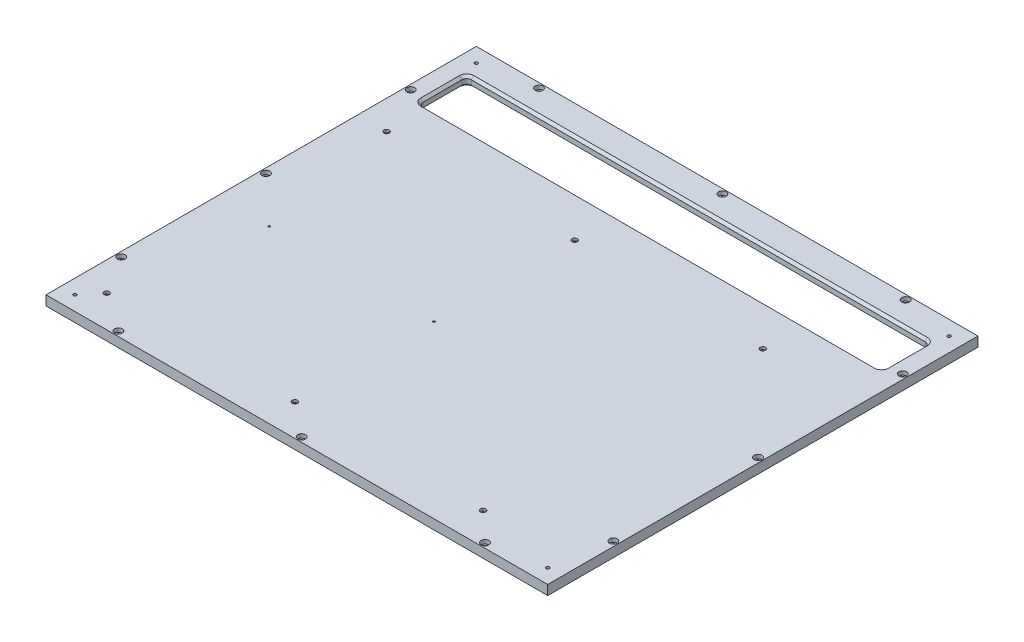
SolidWorks part; units mm, degrees
material "Bakelite Black"
ref_plane "Front" through (0, 0, 0) normal (0, 0, 1) x (1, 0, 0)
ref_plane "Top" through (0, 0, 0) normal (0, 1, 0) x (1, 0, 0)
ref_plane "Right" through (0, 0, 0) normal (1, 0, 0) x (0, 0, -1)
sketch "Sketch1" plane through (0, 0, 0) normal (0, 1, 0) x (1, 0, 0)
  line L1 (0, 0) -> (520, 0)
  line L2 (0, 0) -> (0, 446)
  line L3 (0, 446) -> (520, 446)
  line L4 (520, 0) -> (520, 446)
  dimension "D1" = 520
  dimension "D2" = 446
extrude "Boss-Extrude1" add sketch "Sketch1" along normal blind 10
sketch "Sketch4" plane through (0, 10, 0) normal (0, 1, 0) x (1, 0, 0)
  line L0 (520, 446) -> (0, 446) construction
  line L1 (500, 366) -> (20, 366)
  line L2 (500, 366) -> (500, 416)
  line L3 (500, 416) -> (20, 416)
  line L4 (20, 366) -> (20, 416)
  line L6 (260, 416) -> (260, 0) construction
  line L7 (20, 391) -> (500, 391) construction
  line L8 (0, 0) -> (520, 0) construction
  dimension "D1" = 240
  dimension "D2" = 30
  dimension "D3" = 50
extrude "Cut-Extrude1" cut sketch "Sketch4" against normal blind 10
fillet "Fillet1" radius 5 4 edges at (500, 5, -366) (20, 5, -416) (500, 5, -416) (20, 5, -366)
chamfer "Chamfer1" distance 2.5 angle 45 16 edges at (21.4645, 10, -367.4645) (260, 10, -366) (498.5355, 10, -367.4645) (500, 10, -391) (498.5355, 10, -414.5355) (260, 10, -416) (21.4645, 10, -414.5355) (20, 10, -391) (21.4645, 0, -367.4645) (20, 0, -391) (21.4645, 0, -414.5355) (260, 0, -416) (498.5355, 0, -414.5355) (500, 0, -391) (498.5355, 0, -367.4645) (260, 0, -366)
ref_plane "Plane1" through (260, 0, 0) normal (-1, 0, 0) x (0, 0, 1)
ref_plane "Plane2" through (0, 0, -223) normal (0, 0, 1) x (1, 0, 0)
hole_wizard "CBORE for M4 SHCS1" positions "Sketch5" profile "Sketch6" counterbore size "M4" standard "ANSI Metric"
sketch "Sketch5" plane through (0, 10, 0) normal (0, 1, 0) x (1, 0, 0)
  line L0 (260, 5.5) -> (260, -5.5) construction
  line L1 (-5.5, 223) -> (5.5, 223) construction
  line L3 (0, 0) -> (520, 0) construction
  line L4 (520, 446) -> (0, 446) construction
  line L5 (0, 446) -> (0, 0) construction
  line L6 (520, 0) -> (520, 446) construction
  point P0 (5, 373)
  point P2 (5, 223)
  point P4 (5, 73)
  point P6 (70, 5)
  point P8 (260, 5)
  point P10 (450, 5)
  point P12 (515, 73)
  point P14 (515, 223)
  point P16 (515, 373)
  point P18 (450, 441)
  point P20 (260, 441)
  point P22 (70, 441)
  dimension "D1" = 150
  dimension "D2" = 150
  dimension "D3" = 190
  dimension "D4" = 190
  dimension "D5" = 5
  dimension "D6" = 5
  dimension "D7" = 5
  dimension "D8" = 5
sketch "Sketch6" plane through (5, 10, -373) normal (1, 0, 0) x (0, 0, 1)
  line L0 (0, 0) -> (0, 13.3519)
  line L1 (0, 13.3519) -> (2.25, 12)
  line L2 (2.25, 12) -> (2.25, 4)
  line L3 (2.25, 4) -> (4, 4)
  line L4 (4, 4) -> (4, 0)
  line L5 (4, 0) -> (0, 0)
  line L10 (0, 13.3519) -> (-2.25, 12) construction
  line L11 (0, -6.35) -> (0, 107.95) construction
  dimension "Hole Dia." = 4.5
  dimension "Hole Depth" = 12
  dimension "C'Bore Dia." = 8
  dimension "C'Bore Depth" = 4
  dimension "Drill Angle" = 118
hole_wizard "M4x0.7 Tapped Hole1" positions "Sketch7" profile "Sketch8" tap size "M4x0.7" standard "ANSI Metric" end condition through all
sketch "Sketch7" plane through (0, 10, 0) normal (0, 1, 0) x (1, 0, 0)
  line L0 (520, 446) -> (0, 446) construction
  line L1 (0, 446) -> (0, 0) construction
  line L2 (520, 0) -> (520, 446) construction
  line L3 (0, 0) -> (520, 0) construction
  point P0 (15, 431)
  point P2 (505, 431)
  point P4 (15, 15)
  point P6 (505, 15)
  dimension "D1" = 15
  dimension "D2" = 15
  dimension "D3" = 15
  dimension "D4" = 15
sketch "Sketch8" plane through (15, 10, -431) normal (1, 0, 0) x (0, 0, 1)
  line L0 (0, 0) -> (0, 10)
  line L1 (0, 10) -> (1.65, 10)
  line L2 (1.65, 10) -> (1.65, 0)
  line L5 (1.65, 0) -> (0, 0)
  line L11 (0, -6.35) -> (0, 107.95) construction
  dimension "Thru Tap Drill Dia." = 3.3
  dimension "Thru Tap Drill Depth" = 10
cosmetic thread "Hole Thread1" parameters "D2"=4
cosmetic thread "Hole Thread2" parameters "D2"=4
cosmetic thread "Hole Thread3" parameters "D2"=4
cosmetic thread "Hole Thread4" parameters "D2"=4
hole_wizard "CBORE for M2.5 SHCS1" positions "Sketch9" profile "Sketch10" counterbore size "M2.5" standard "ANSI Metric" end condition through all
sketch "Sketch9" plane through (0, 10, 0) normal (0, 1, 0) x (1, 0, 0)
  line L0 (-5.5, 223) -> (5.5, 223) construction
  line L1 (260, 5.5) -> (260, -5.5) construction
  point P0 (30, 33)
  point P7 (225, 33)
  point P9 (420, 33)
  point P11 (420, 323)
  point P13 (225, 323)
  point P15 (30, 323)
  dimension "D1" = 190
  dimension "D2" = 230
  dimension "D3" = 290
  dimension "D4" = 195
  dimension "D5" = 195
sketch "Sketch10" plane through (30, 10, -33) normal (1, 0, 0) x (0, 0, 1)
  line L0 (0, 0) -> (0, 10)
  line L1 (0, 10) -> (1.45, 10)
  line L3 (1.45, 10) -> (1.45, 2.5)
  line L4 (1.45, 2.5) -> (2.75, 2.5)
  line L5 (2.75, 2.5) -> (2.75, 0)
  line L7 (2.75, 0) -> (0, 0)
  line L11 (0, -6.35) -> (0, 107.95) construction
  dimension "Thru Hole Dia." = 2.9
  dimension "Thru Hole Depth" = 10
  dimension "C'Bore Dia." = 5.5
  dimension "C'Bore Depth" = 2.5
hole_wizard "M2.5x0.45 Tapped Hole1" positions "Sketch11" profile "Sketch12" tap size "M2.5x0.45" standard "ANSI Metric" end condition through all
sketch "Sketch11" plane through (0, 10, 0) normal (0, 1, 0) x (1, 0, 0)
  line L0 (-5.5, 223) -> (5.5, 223) construction
  line L1 (260, 5.5) -> (260, -5.5) construction
  point P0 (54.288, 177.0876)
  point P2 (225.088, 177.0876)
  dimension "D1" = 170.8
  dimension "D2" = 45.9124
  dimension "D3" = 205.712
sketch "Sketch12" plane through (54.288, 10, -177.0876) normal (1, 0, 0) x (0, 0, 1)
  line L0 (0, 0) -> (0, 10)
  line L1 (0, 10) -> (1.025, 10)
  line L2 (1.025, 10) -> (1.025, 0)
  line L5 (1.025, 0) -> (0, 0)
  line L11 (0, -6.35) -> (0, 107.95) construction
  dimension "Thru Tap Drill Dia." = 2.05
  dimension "Thru Tap Drill Depth" = 10
cosmetic thread "Hole Thread5" parameters "D2"=2.5
cosmetic thread "Hole Thread6" parameters "D2"=2.5
